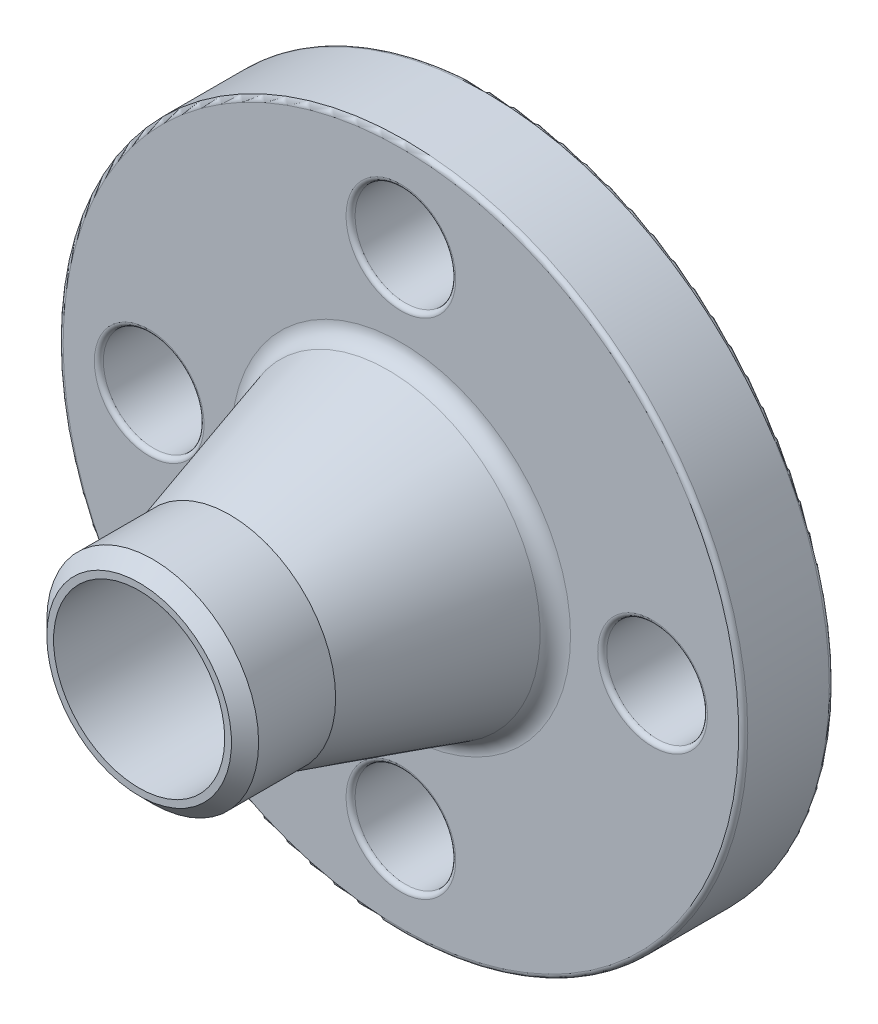
SolidWorks part; units mm, degrees
ref_plane "Front Plane" through (0, 0, 0) normal (0, 0, 1) x (1, 0, 0)
ref_plane "Top Plane" through (0, 0, 0) normal (0, 1, 0) x (1, 0, 0)
ref_plane "Right Plane" through (0, 0, 0) normal (1, 0, 0) x (0, 0, -1)
sketch "Sketch1" plane through (0, 0, 0) normal (1, 0, 0) x (0, 0, -1)
  line L0 (-27.7813, 0) -> (27.7813, 0) construction
  line L1 (27.7813, 13.4937) -> (27.7812, 53.975)
  line L2 (27.7812, 53.975) -> (13.4938, 53.975)
  line L3 (13.4938, 53.975) -> (13.4937, 24.6062)
  line L4 (13.4937, 24.6062) -> (-13.4938, 16.7005)
  line L5 (-13.4938, 16.7005) -> (-27.7812, 16.7005)
  line L6 (-27.7812, 16.7005) -> (-27.7813, 13.4937)
  line L7 (-27.7813, 13.4937) -> (27.7813, 13.4937)
  circle A0 centre (27.7813, 39.6875) radius 7.9375
  point P16 (27.7813, 39.6875)
  dimension "Bolt Size" = 15.875
  dimension "Flange OD" = 107.95
  dimension "Pipe Size" = 26.9875
  dimension "Hub at Chimney" = 33.401
  dimension "Hub OD Base" = 49.2125
  dimension "Flange Thickness" = 14.2875
  dimension "Length" = 55.5625
  dimension "Bolt O Diameter" = 79.375
sketch "Sketch2" plane through (0, 0, 0) normal (1, 0, 0) x (0, 0, -1)
  line L0 (-27.7812, 16.7005) -> (-27.7813, 13.4937) construction
  line L1 (-13.4938, 16.7005) -> (-27.7812, 16.7005) construction
  line L2 (13.4937, 24.6062) -> (-13.4938, 16.7005) construction
  line L3 (13.4938, 53.975) -> (13.4937, 24.6062) construction
  line L4 (27.7812, 53.975) -> (13.4938, 53.975) construction
  line L5 (27.7813, 13.4937) -> (27.7812, 53.975) construction
  line L6 (-27.7813, 13.4937) -> (27.7813, 13.4937) construction
  line L7 (-27.7812, 16.7005) -> (-27.7813, 13.4937)
  line L8 (-13.4938, 16.7005) -> (-27.7812, 16.7005)
  line L9 (13.4937, 24.6062) -> (-13.4938, 16.7005)
  line L10 (13.4938, 53.975) -> (13.4937, 24.6062)
  line L11 (27.7812, 53.975) -> (13.4938, 53.975)
  line L12 (27.7813, 13.4937) -> (27.7812, 53.975)
  line L13 (-27.7813, 13.4937) -> (27.7813, 13.4937)
revolve "Revolve1" add sketch "Sketch2" angle 360 about L0
sketch "Sketch3" plane through (0, 0, -13.4937) normal (0, 0, 1) x (1, 0, 0)
  line L0 (-13.4937, 0) -> (-16.7005, 0) construction
  circle A0 centre (0, 39.6875) radius 7.9375
  circle A1 centre (0, 0) radius 13.4937 construction
  circle A2 centre (0, 0) radius 16.7005 construction
  circle A5 centre (0, 0) radius 16.7005 construction
  dimension "D1" = 15.875
extrude "Cut-Extrude1" cut sketch "Sketch3" against normal through all
pattern_circular "CirPattern1" count 4 over 360 about axis through (0, 0, 0) along (0, 0, 1) of "Cut-Extrude1"
fillet "Fillet1" radius 2.8575 1 edges at (24.6062, 0, -13.4937)
chamfer "Chamfer1" distance 2.1431 angle 45 1 edges at (16.7005, 0, 27.7812)
fillet "Fillet2" radius 0.7144 11 edges at (53.975, 0, -27.7812) (53.975, 0, -13.4937) (13.4937, 0, -27.7813) (7.9375, 39.6875, -27.7813) (39.6875, -7.9375, -27.7813) (-39.6875, 7.9375, -27.7813) (-7.9375, -39.6875, -27.7813) (7.9375, 39.6875, -13.4937) (39.6875, -7.9375, -13.4937) (-39.6875, 7.9375, -13.4937) (-7.9375, -39.6875, -13.4937)
equation "\"D1@Sketch3\"=\"bolt size@sketch1\""
equation "\"D1@Fillet1\"=\"Flange Thickness@Sketch1\"*0.2"
equation "\"D1@Chamfer1\"=\"Flange Thickness@Sketch1\"*0.15"
equation "\"D1@Fillet2\"=\"flange thickness@sketch1\"*0.05"
